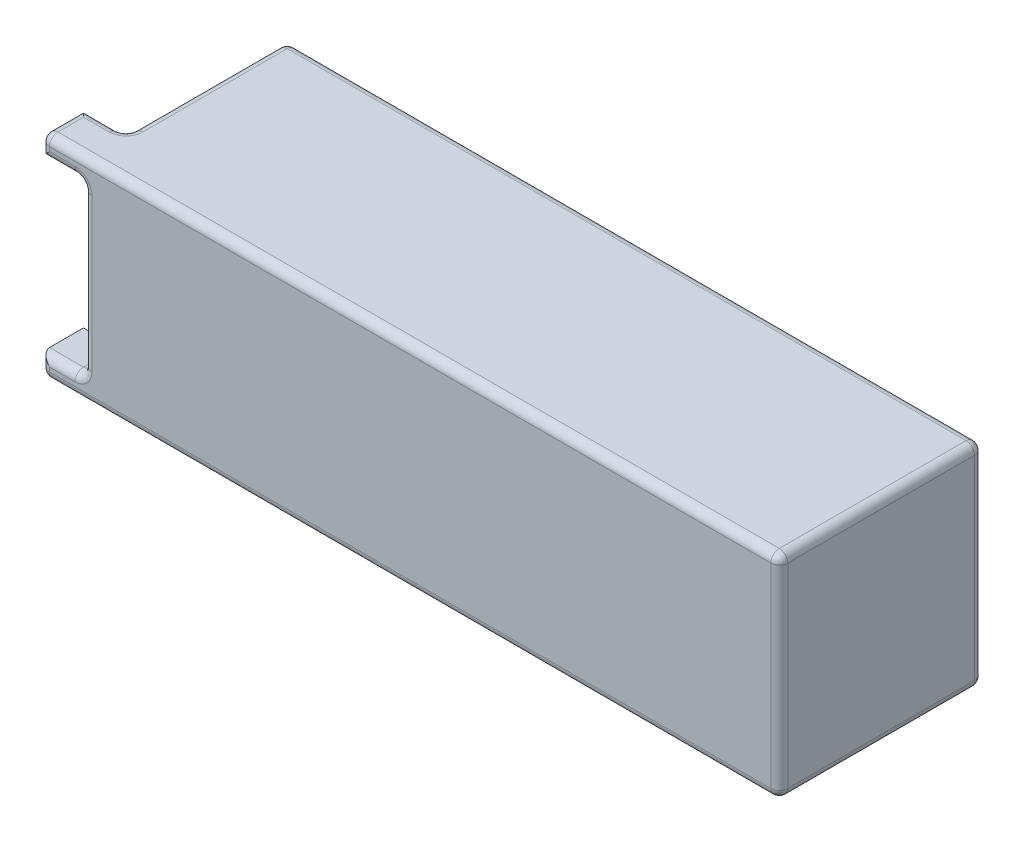
SolidWorks part; units mm, degrees
ref_plane "Front Plane" through (0, 0, 0) normal (0, 0, 1) x (1, 0, 0)
ref_plane "Top Plane" through (0, 0, 0) normal (0, 1, 0) x (1, 0, 0)
ref_plane "Right Plane" through (0, 0, 0) normal (1, 0, 0) x (0, 0, -1)
sketch "Sketch1" plane through (0, 0, 0) normal (0, 0, 1) x (1, 0, 0)
  line L1 (-82, 25) -> (82, 25)
  line L2 (-82, 25) -> (-82, -25)
  line L3 (-82, -25) -> (82, -25)
  line L4 (82, 25) -> (82, -25)
  line L5 (-82, 25) -> (82, -25) construction
  line L6 (-82, -25) -> (82, 25) construction
  point P0 (0, 0)
  dimension "D1" = 164
  dimension "D2" = 50
extrude "Boss-Extrude1" add sketch "Sketch1" along normal blind 48
sketch "Sketch2" plane through (-82, 0, 0) normal (-1, 0, 0) x (0, 0, 1)
  line L0 (35, 0) -> (30.3912, 0) construction
  line L5 (48, -25) -> (38, -25)
  line L6 (48, -25) -> (48, -20)
  line L7 (48, -20) -> (38, -20)
  line L8 (38, -25) -> (38, -20)
  line L10 (38, 25) -> (38, 20)
  line L11 (48, 20) -> (38, 20)
  line L12 (48, 25) -> (48, 20)
  line L13 (48, 25) -> (38, 25)
  dimension "D3" = 10
  dimension "D4" = 5
extrude "Boss-Extrude2" add sketch "Sketch2" along normal blind 10
fillet "Fillet1" radius 2 24 edges at (-82, 0, 48) (-82, 25, 19) (-82, 22.5, 38) (-87, 25, 38) (-5, -25, 48) (-82, 20, 43) (-87, 20, 48) (-92, 25, 43) (-92, 22.5, 48) (-82, -25, 19) (-82, -20, 43) (-87, -20, 48) (-82, -22.5, 38) (-87, -25, 38) (-92, -22.5, 48) (-92, -25, 43) (82, 0, 48) (0, -25, 0) (-82, 0, 0) (0, 25, 0) (82, 0, 0) (82, -25, 24) (82, 25, 24) (-5, 25, 48)
